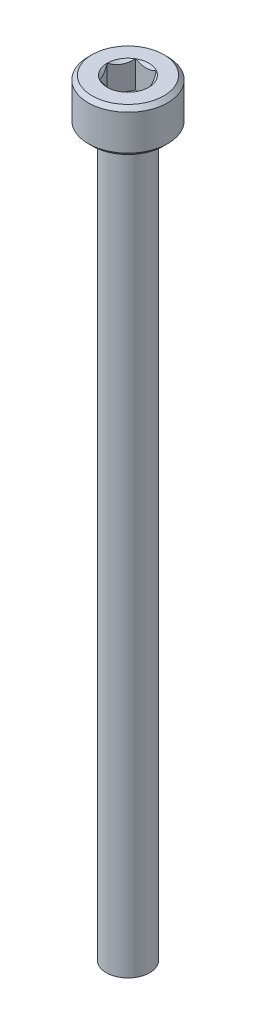
SolidWorks part; units mm, degrees
ref_plane "Front" through (0, 0, 0) normal (0, 0, 1) x (1, 0, 0)
ref_plane "Top" through (0, 0, 0) normal (0, 1, 0) x (1, 0, 0)
ref_plane "Right" through (0, 0, 0) normal (1, 0, 0) x (0, 0, -1)
sketch "Sketch1" plane through (0, 0, 0) normal (0, 1, 0) x (1, 0, 0)
  circle A0 centre (0, 0) radius 2.75
  dimension "D1" = 5.5
extrude "Boss-Extrude1" add sketch "Sketch1" along normal blind 3
sketch "Sketch2" plane through (0, 3, 0) normal (0, 1, 0) x (1, 0, 0)
  line L1 (0.7217, 1.25) -> (-0.7217, 1.25)
  line L2 (-0.7217, 1.25) -> (-1.4434, 0)
  line L3 (-1.4434, 0) -> (-0.7217, -1.25)
  line L4 (-0.7217, -1.25) -> (0.7217, -1.25)
  line L5 (0.7217, -1.25) -> (1.4434, 0)
  line L6 (1.4434, 0) -> (0.7217, 1.25)
  circle A0 centre (0, 0) radius 1.25 construction
  point P10 (0, 1.25)
  dimension "D1" = 2.5
extrude "Cut-Extrude1" cut sketch "Sketch2" against normal blind 1.88
sketch "Sketch5" plane through (0, 3, 0) normal (0, 1, 0) x (1, 0, 0)
  circle A0 centre (0, 0) radius 1.4434
extrude "Cut-Extrude2" cut sketch "Sketch5" against normal through all draft 45
chamfer "Chamfer1" distance 0.275 angle 45 2 edges at (0, 0, 2.75) (0, 3, 2.75)
sketch "草图1" plane through (0, 0, 0) normal (0, -1, 0) x (-1, 0, 0)
  circle A0 centre (0, 0) radius 1.5
  dimension "D1" = 3
extrude "凸台-拉伸1" add sketch "草图1" along normal blind 50
